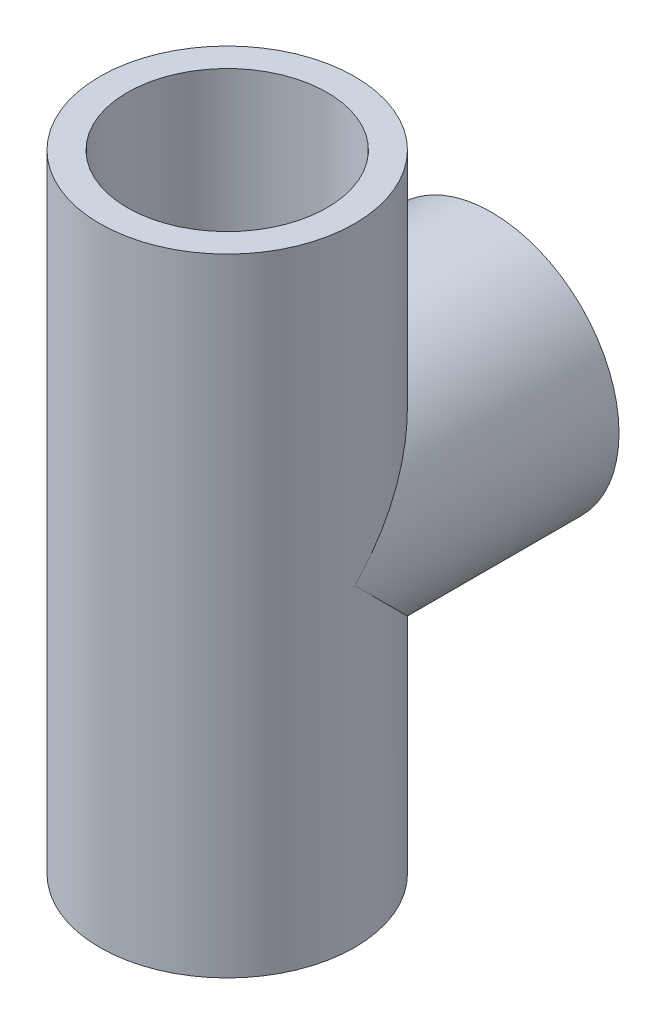
SolidWorks part; units mm, degrees
ref_plane "Front Plane" through (0, 0, 0) normal (0, 0, 1) x (1, 0, 0)
ref_plane "Top Plane" through (0, 0, 0) normal (0, 1, 0) x (1, 0, 0)
ref_plane "Right Plane" through (0, 0, 0) normal (1, 0, 0) x (0, 0, -1)
sketch "Sketch1" plane through (0, 0, 0) normal (0, 1, 0) x (1, 0, 0)
  circle A0 centre (0, 0) radius 11.43
  circle A1 centre (0, 0) radius 17.145
  dimension "D1" = 34.29
  dimension "D2" = 22.86
extrude "Boss-Extrude1" add sketch "Sketch1" along normal blind 84.328
sketch "Sketch2" plane through (0, 0, 0) normal (0, 0, 1) x (1, 0, 0)
  line L0 (-17.145, 0) -> (17.145, 84.328) construction
  circle A0 centre (0, 42.164) radius 17.145
  circle A1 centre (0, 42.164) radius 11.43
  dimension "D1" = 22.86
  dimension "D2" = 34.29
extrude "Boss-Extrude2" add sketch "Sketch2" against normal blind 35.56
sketch "Sketch3" plane through (0, 84.328, 0) normal (0, 1, 0) x (1, 0, 0)
  circle A0 centre (0, 0) radius 11.43
  dimension "D1" = 22.86
extrude "Cut-Extrude1" cut sketch "Sketch3" against normal through all
sketch "Sketch4" plane through (0, 0, -35.56) normal (0, 0, -1) x (-1, 0, 0)
  circle A0 centre (0, 42.164) radius 11.43 construction
  circle A1 centre (0, 42.164) radius 11.43
extrude "Cut-Extrude2" cut sketch "Sketch4" against normal blind 35.56
sketch "Sketch5" plane through (0, 84.328, 0) normal (0, 1, 0) x (1, 0, 0)
  circle A0 centre (0, 0) radius 13.4366
  dimension "D1" = 26.8732
extrude "Cut-Extrude3" cut sketch "Sketch5" against normal blind 20.6375
sketch "Sketch6" plane through (0, 0, 0) normal (0, -1, 0) x (1, 0, 0)
  circle A0 centre (0, 0) radius 13.4366
  dimension "D1" = 26.8732
extrude "Cut-Extrude4" cut sketch "Sketch6" against normal blind 20.6375
sketch "Sketch7" plane through (0, 0, -35.56) normal (0, 0, -1) x (-1, 0, 0)
  circle A0 centre (0, 42.164) radius 13.4366
  dimension "D1" = 26.8732
extrude "Cut-Extrude5" cut sketch "Sketch7" against normal blind 20.6375
